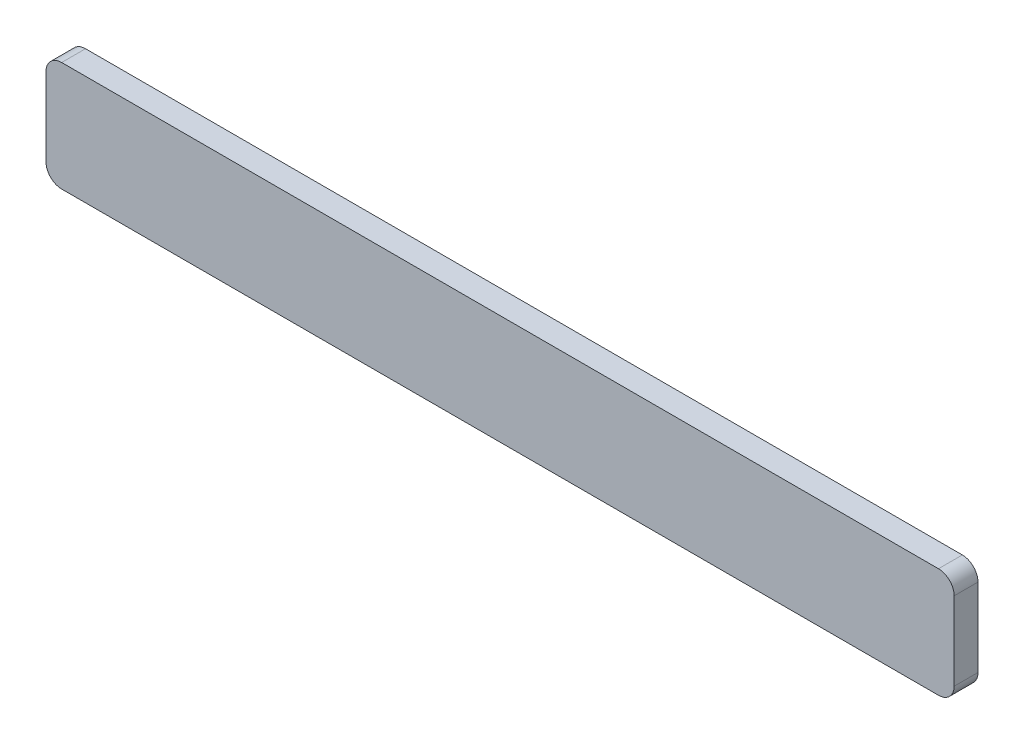
SolidWorks part; units mm, degrees
ref_plane "Front Plane" through (0, 0, 0) normal (0, 0, 1) x (1, 0, 0)
ref_plane "Top Plane" through (0, 0, 0) normal (0, 1, 0) x (1, 0, 0)
ref_plane "Right Plane" through (0, 0, 0) normal (1, 0, 0) x (0, 0, -1)
sketch "Sketch1" plane through (0, 0, 0) normal (0, 0, 1) x (1, 0, 0)
  line L1 (-29, 3.5) -> (29, 3.5)
  line L2 (-29, 3.5) -> (-29, -3.5)
  line L3 (-29, -3.5) -> (29, -3.5)
  line L4 (29, 3.5) -> (29, -3.5)
  line L5 (-29, 3.5) -> (29, -3.5) construction
  line L6 (-29, -3.5) -> (29, 3.5) construction
  point P0 (0, 0)
  dimension "D1" = 58
  dimension "D2" = 7
extrude "Boss-Extrude1" add sketch "Sketch1" along normal blind 1.524
fillet "Fillet1" radius 1 4 edges at (29, -3.5, 0.762) (29, 3.5, 0.762) (-29, -3.5, 0.762) (-29, 3.5, 0.762)
